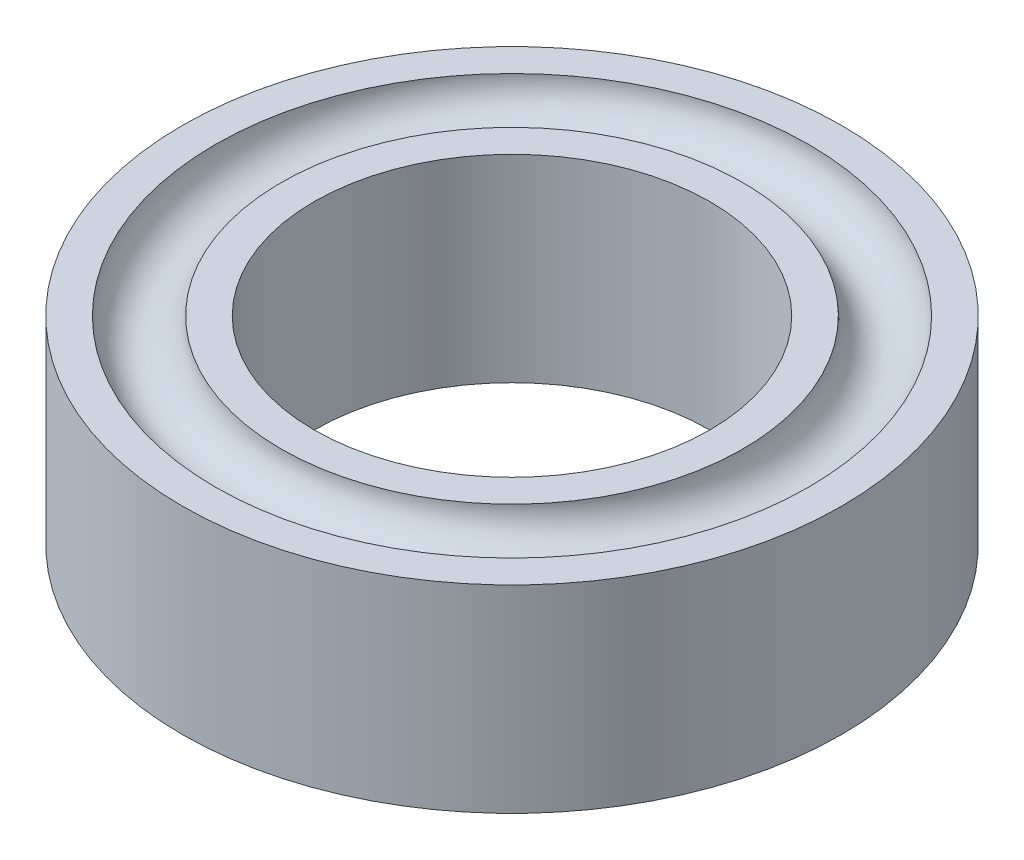
SolidWorks part; units mm, degrees
ref_plane "Front Plane" through (0, 0, 0) normal (0, 0, 1) x (1, 0, 0)
ref_plane "Top Plane" through (0, 0, 0) normal (0, 1, 0) x (1, 0, 0)
ref_plane "Right Plane" through (0, 0, 0) normal (1, 0, 0) x (0, 0, -1)
sketch "Sketch1" plane through (0, 0, 0) normal (0, 0, 1) x (1, 0, 0)
  line L0 (0, 2.0104) -> (0, -1.7188) construction
  line L1 (0, 1.5) -> (3.5, 1.5)
  line L2 (4.5, 1.5) -> (5, 1.5)
  line L3 (5, 1.5) -> (5, -1.5)
  line L4 (5, -1.5) -> (4.5, -1.5)
  line L5 (3.5, -1.5) -> (0, -1.5)
  line L6 (0, -1.5) -> (0, 1.5)
  arc A0 (3.5, 1.5) -> (4.5, 1.5) centre (4, 1.5) ccw
  arc A1 (4.5, -1.5) -> (3.5, -1.5) centre (4, -1.5) ccw
  point P12 (3, -1.4132)
  point P14 (4.5556, -1.3785)
  point P15 (0, 0)
  point P16 (0, 0)
  point P17 (0, 0)
  point P18 (0, 0)
  point P19 (3.718, 1.5)
  dimension "D4" = 0.5
  dimension "D1" = 5
  dimension "D2" = 3
  dimension "D3" = 4
revolve "Revolve1" add sketch "Sketch1" angle 360 about L0
sketch "Sketch2" plane through (0, 1.5, 0) normal (0, 1, 0) x (1, 0, 0)
  circle A0 centre (0, 0) radius 3
  dimension "D1" = 6
extrude "Cut-Extrude1" cut sketch "Sketch2" against normal blind 10
